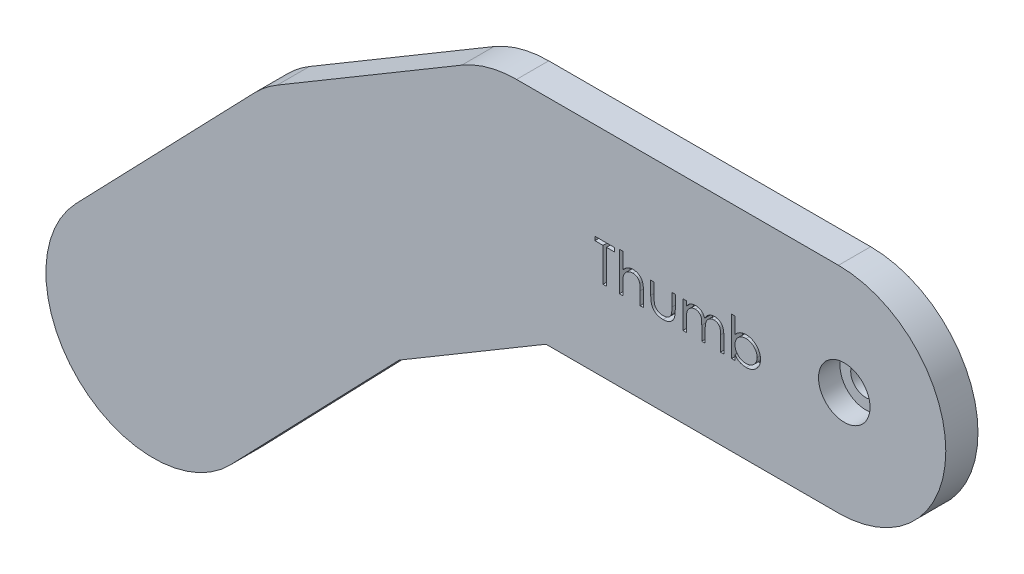
SolidWorks part; units mm, degrees
ref_plane "Front Plane" through (0, 0, 0) normal (0, 0, 1) x (1, 0, 0)
ref_plane "Top Plane" through (0, 0, 0) normal (0, 1, 0) x (1, 0, 0)
ref_plane "Right Plane" through (0, 0, 0) normal (1, 0, 0) x (0, 0, -1)
sketch "Sketch1" plane through (0, 0, 0) normal (0, 0, 1) x (1, 0, 0)
  line L0 (0, 0) -> (30, 0) construction
  line L2 (0, 10) -> (30, 10)
  line L3 (0, -10) -> (30, -10)
  arc A0 (0, 10) -> (0, -10) centre (0, 0) ccw
  arc A1 (30, -10) -> (30, 10) centre (30, 0) ccw
  point P5 (15, 0)
extrude "Boss-Extrude1" add sketch "Sketch1" along normal blind 3
sketch "Sketch2" plane through (0, 0, 0) normal (0, 0, 1) x (1, 0, 0)
  line L0 (0, 0) -> (-17.1984, -10.2085) construction
  line L2 (5.1043, -8.5992) -> (-12.0942, -18.8077)
  line L3 (-5.1043, 8.5992) -> (-22.3027, -1.6093)
  arc A0 (5.1043, -8.5992) -> (-5.1043, 8.5992) centre (0, 0) ccw
  arc A1 (-22.3027, -1.6093) -> (-12.0942, -18.8077) centre (-17.1984, -10.2085) ccw
  point P5 (-8.5992, -5.1043)
extrude "Boss-Extrude2" add sketch "Sketch2" along normal blind 3
sketch "Sketch3" plane through (0, 0, 0) normal (0, 0, 1) x (1, 0, 0)
  line L0 (-17.1984, -10.2085) -> (-33.8549, -27.4874) construction
  line L2 (-9.9989, -17.1487) -> (-26.6554, -34.4276)
  line L3 (-24.398, -3.2683) -> (-41.0545, -20.5472)
  arc A0 (-9.9989, -17.1487) -> (-24.398, -3.2683) centre (-17.1984, -10.2085) ccw
  arc A1 (-41.0545, -20.5472) -> (-26.6554, -34.4276) centre (-33.8549, -27.4874) ccw
  point P5 (-25.5267, -18.848)
extrude "Boss-Extrude4" add sketch "Sketch3" along normal blind 3
sketch "Sketch4" plane through (0, 0, 0) normal (0, 0, 1) x (1, 0, 0)
  circle A0 centre (30.5386, 0) radius 1.4
extrude "Cut-Extrude5" cut sketch "Sketch4" along normal blind 3
sketch "Sketch5" plane through (0, 0, 3) normal (0, 0, 1) x (1, 0, 0)
  circle A0 centre (30.5386, 0) radius 2.4
extrude "Cut-Extrude6" cut sketch "Sketch5" against normal blind 2
sketch "Sketch6" plane through (0, 0, 3) normal (0, 0, 1) x (1, 0, 0)
  text T0 "Thumb"
extrude "Cut-Extrude7" cut sketch "Sketch6" against normal blind 1
